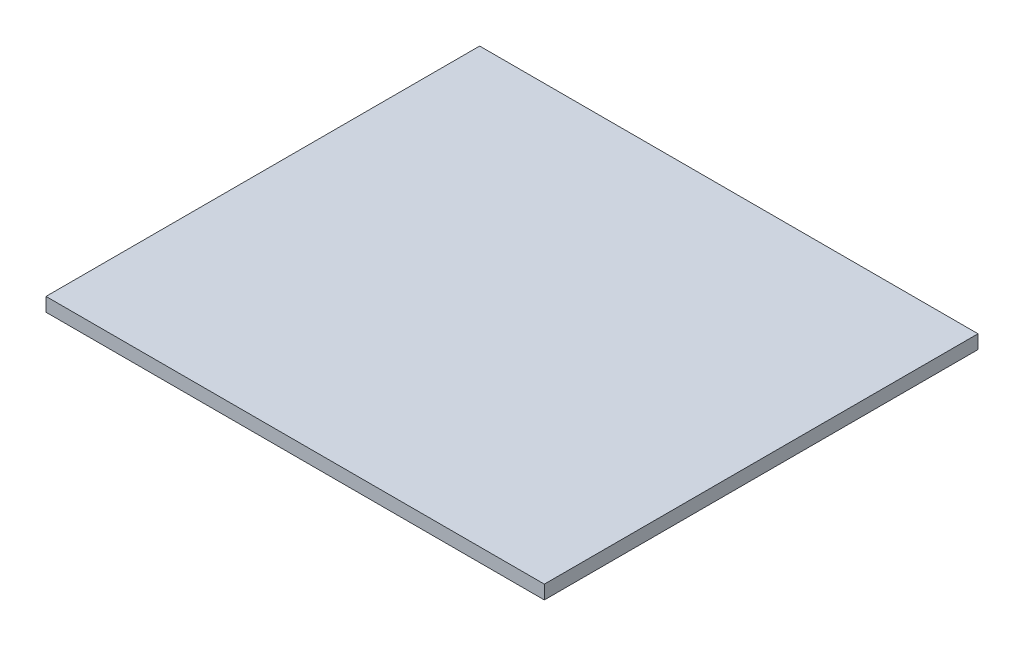
SolidWorks part; units mm, degrees
ref_plane "Front Plane" through (0, 0, 0) normal (0, 0, 1) x (1, 0, 0)
ref_plane "Top Plane" through (0, 0, 0) normal (0, 1, 0) x (1, 0, 0)
ref_plane "Right Plane" through (0, 0, 0) normal (1, 0, 0) x (0, 0, -1)
sketch "Sketch1" plane through (0, 0, 0) normal (0, 1, 0) x (1, 0, 0)
  line L1 (-199.2391, 36.9171) -> (154.7657, 36.9171)
  line L2 (-199.2391, 36.9171) -> (-199.2391, -271.1341)
  line L3 (-199.2391, -271.1341) -> (154.7657, -271.1341)
  line L4 (154.7657, 36.9171) -> (154.7657, -271.1341)
  dimension "D1" = 354.0049
  dimension "D2" = 308.0512
extrude "Boss-Extrude1" add sketch "Sketch1" along normal blind 9.7536
equation "\"D2@Sketch1\"=\"Base Width@Assembled Container.Assembly\""
equation "\"D1@Sketch1\"=\"Base Length@Assembled Container.Assembly\""
equation "\"D1@Boss-Extrude1\"=\"Acrylic Thickness@Assembled Container.Assembly\""
